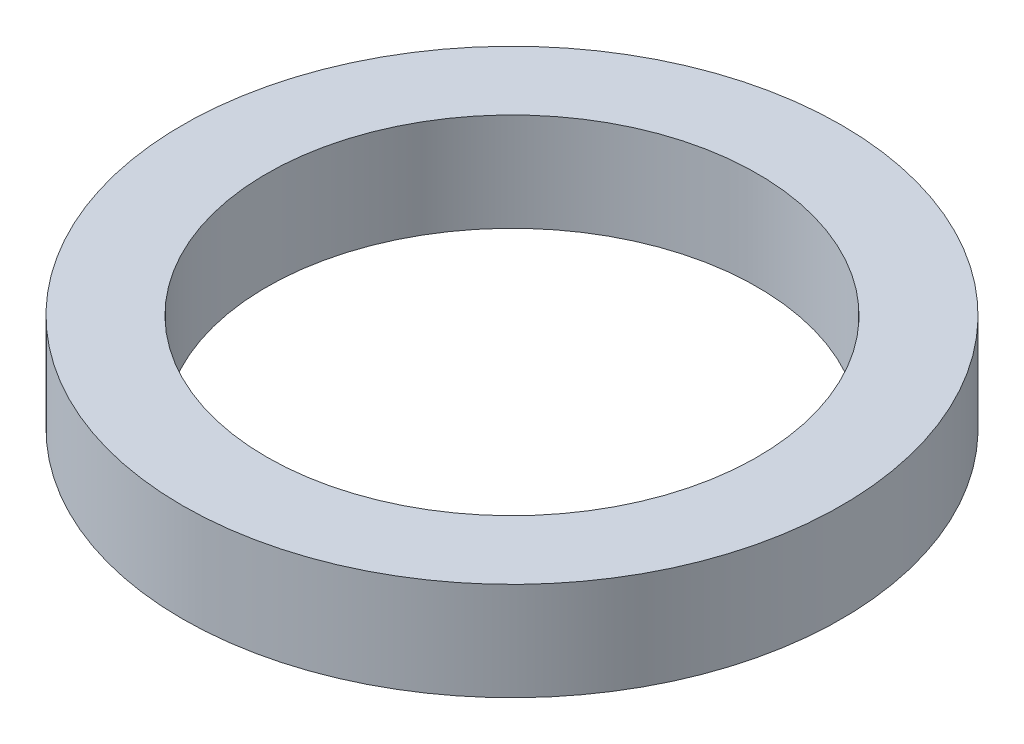
SolidWorks part; units mm, degrees
ref_plane "Front Plane" through (0, 0, 0) normal (0, 0, 1) x (1, 0, 0)
ref_plane "Top Plane" through (0, 0, 0) normal (0, 1, 0) x (1, 0, 0)
ref_plane "Right Plane" through (0, 0, 0) normal (1, 0, 0) x (0, 0, -1)
sketch "Sketch1" plane through (0, 0, 0) normal (0, 1, 0) x (1, 0, 0)
  circle A0 centre (0, 0) radius 23.5
  circle A1 centre (0, 0) radius 17.5
  dimension "D1" = 35
  dimension "D2" = 47
extrude "Boss-Extrude1" add sketch "Sketch1" along normal mid plane 7
